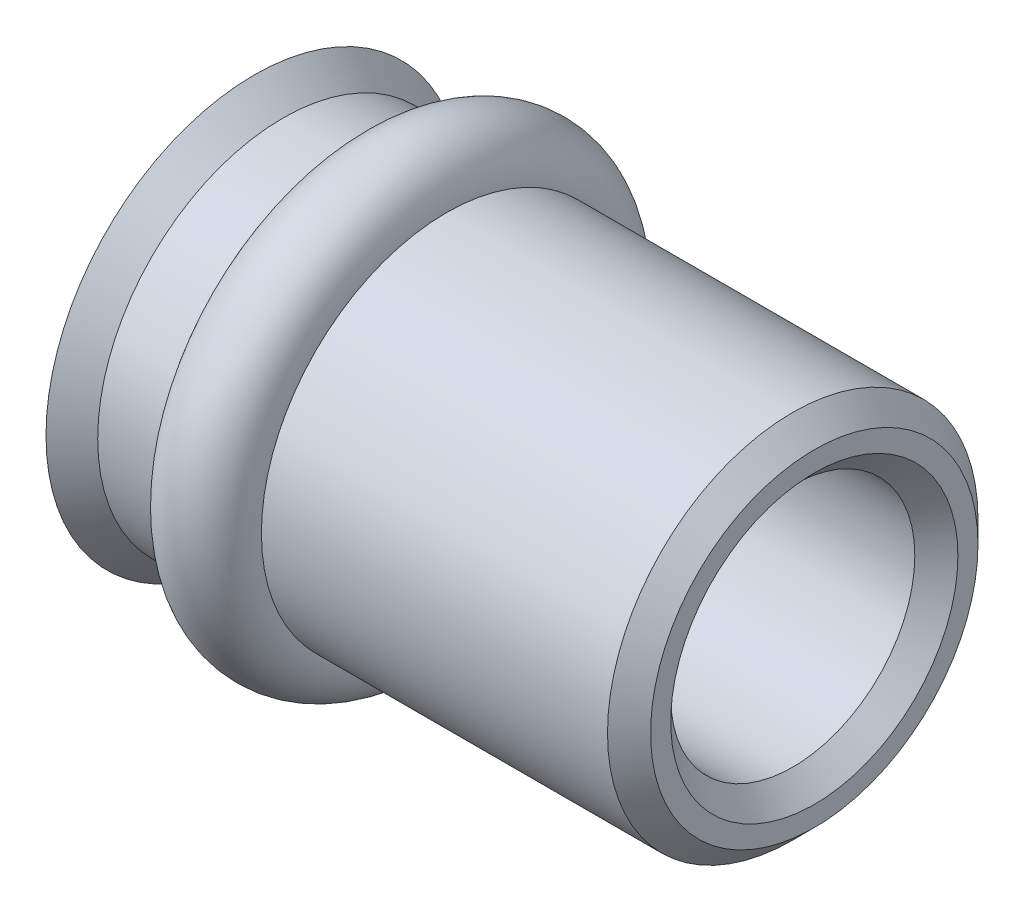
SolidWorks part; units mm, degrees
material "12Х18Н10Т ГОСТ 4543-71"
ref_plane "Спереди" through (0, 0, 0) normal (0, 0, 1) x (1, 0, 0)
ref_plane "Сверху" through (0, 0, 0) normal (0, 1, 0) x (1, 0, 0)
ref_plane "Справа" through (0, 0, 0) normal (1, 0, 0) x (0, 0, -1)
sketch "Эскиз1" plane through (0, 0, 0) normal (0, 0, 1) x (1, 0, 0)
  line L0 (0, 0) -> (-3.1667, 0) construction
  line L1 (0, 7.25) -> (0, 5.25)
  line L2 (0, 5.25) -> (9, 5.25)
  line L3 (9, 5.25) -> (10, 4.25)
  line L4 (10, 4.25) -> (18.75, 4.25)
  line L5 (19.5, 5) -> (19.5, 5.7)
  line L6 (0, 7.25) -> (1, 6.45)
  line L7 (1, 6.45) -> (3.5, 6.45)
  line L8 (18.75, 4.25) -> (19.5, 5)
  line L9 (18.75, 6.45) -> (19.5, 5.7)
  line L10 (0, 7.25) -> (5.1, 7.25) construction
  line L11 (6.7, 6.45) -> (18.75, 6.45)
  line L12 (5.1, 8.05) -> (5.1, 6.45) construction
  arc A0 (3.5, 6.45) -> (6.7, 6.45) centre (5.1, 6.45) cw
  point P8 (19.5, 4.25)
  point P10 (19.5, 6.45)
  dimension "D10" = 3.5
  dimension "D1" = 12.9
  dimension "D2" = 8.5
  dimension "D3" = 1.2
  dimension "D4" = 14.5
  dimension "D5" = 1
  dimension "D6" = 19.5
  dimension "D7" = 9
  dimension "D8" = 45
  dimension "D9" = 10.5
revolve "Повернуть1" add sketch "Эскиз1" angle 360 about L0
cosmetic thread "Резьба" parameters "D2"=10
